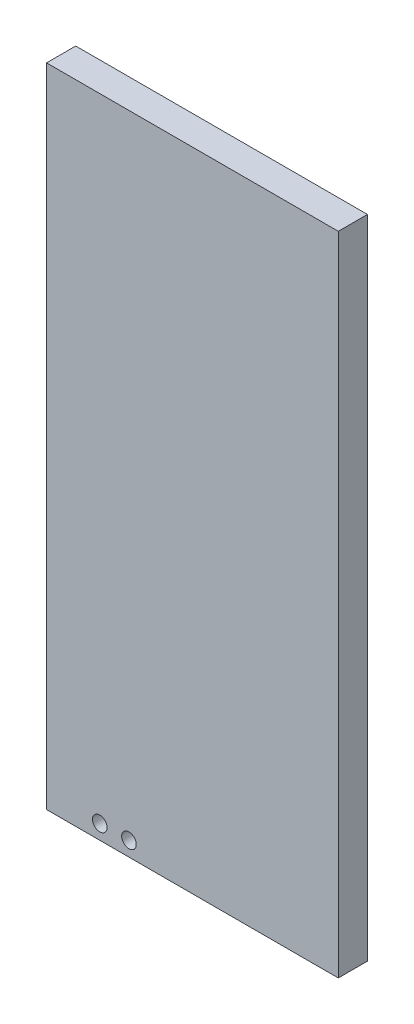
SolidWorks part; units mm, degrees
ref_plane "Plan de face" through (0, 0, 0) normal (0, 0, 1) x (1, 0, 0)
ref_plane "Plan de dessus" through (0, 0, 0) normal (0, 1, 0) x (1, 0, 0)
ref_plane "Plan de droite" through (0, 0, 0) normal (1, 0, 0) x (0, 0, -1)
sketch "Esquisse3" plane through (0, 0, 0) normal (0, 0, 1) x (1, 0, 0)
  line L0 (30, -66.5) -> (-30, 66.5) construction
  line L1 (-30, 66.5) -> (30, 66.5)
  line L2 (-30, 66.5) -> (-30, -66.5)
  line L3 (-30, -66.5) -> (30, -66.5)
  line L4 (30, 66.5) -> (30, -66.5)
  line L5 (30, 66.5) -> (-30, -66.5) construction
  dimension "D1" = 60
  dimension "D2" = 133
extrude "Boss.-Extru.2" add sketch "Esquisse3" along normal blind 6
sketch "Esquisse4" plane through (0, 0, 0) normal (0, 0, -1) x (-1, 0, 0)
  line L0 (30, -66.5) -> (-30, -66.5) construction
  line L1 (30, 66.5) -> (30, -66.5) construction
  circle A0 centre (13.05, -63.5) radius 1.5
  circle A1 centre (19.05, -63.5) radius 1.5
  dimension "D5" = 3
  dimension "D6" = 3
  dimension "D1" = 3
  dimension "D2" = 3
  dimension "D3" = 6
  dimension "D4" = 10.95
extrude "Enlèv. mat.-Extru.1" cut sketch "Esquisse4" against normal through all
sketch "Esquisse5" plane through (0, 0, 0) normal (0, 0, -1) x (-1, 0, 0)
  circle A0 centre (13.05, -63.5) radius 2.995
  circle A1 centre (19.05, -63.5) radius 2.995
  dimension "D1" = 5.99
  dimension "D2" = 5.99
extrude "Enlèv. mat.-Extru.2" cut sketch "Esquisse5" against normal blind 3
